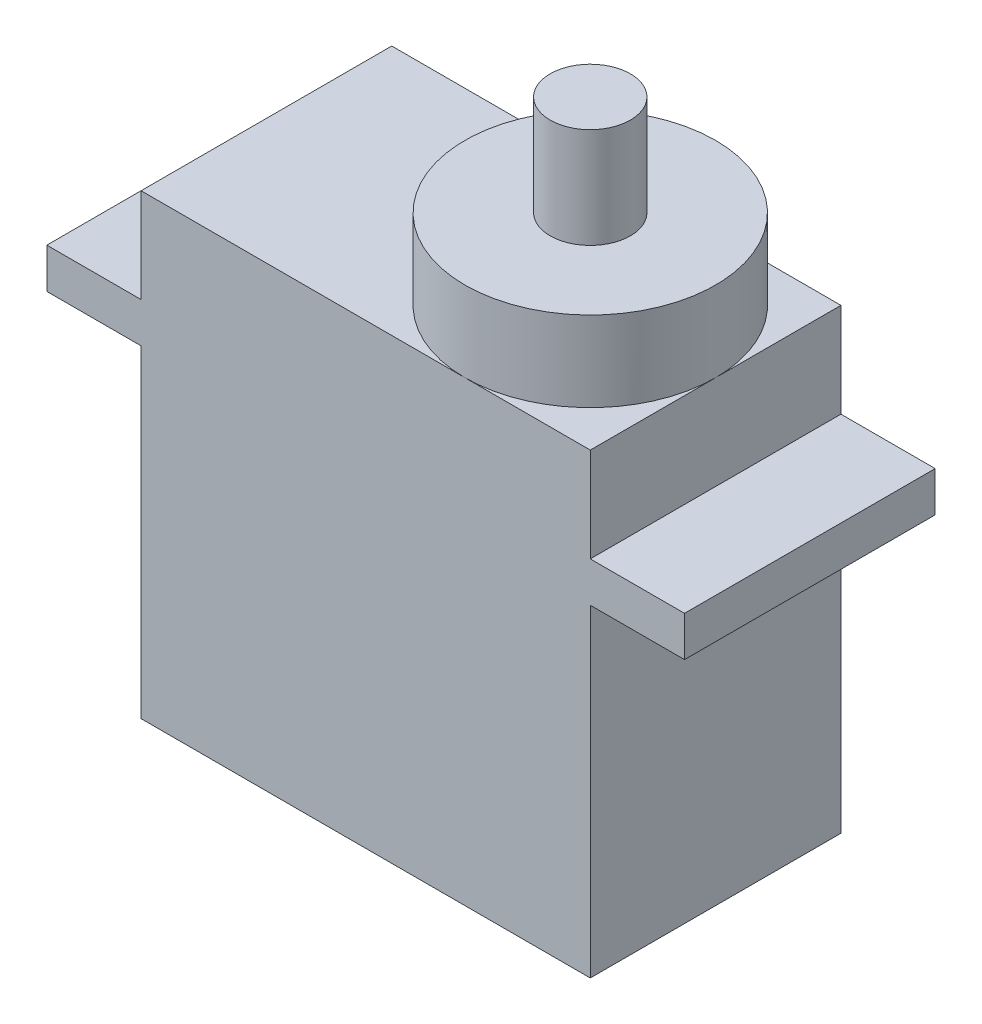
SolidWorks part; units mm, degrees
ref_plane "前视基准面" through (0, 0, 0) normal (0, 0, 1) x (1, 0, 0)
ref_plane "上视基准面" through (0, 0, 0) normal (0, 1, 0) x (1, 0, 0)
ref_plane "右视基准面" through (0, 0, 0) normal (1, 0, 0) x (0, 0, -1)
sketch "草图1" plane through (0, 0, 0) normal (0, 0, 1) x (1, 0, 0)
  line L1 (11.2, -11.4) -> (-11.2, -11.4)
  line L2 (11.2, -11.4) -> (11.2, 11.4)
  line L3 (11.2, 11.4) -> (-11.2, 11.4)
  line L4 (-11.2, -11.4) -> (-11.2, 11.4)
  line L5 (0, 11.4) -> (0, -11.4) construction
  line L6 (11.2, 0) -> (-11.2, 0) construction
  point P0 (0, 0)
  dimension "D1" = 22.8
  dimension "D2" = 22.4
extrude "凸台-拉伸1" add sketch "草图1" along normal mid plane 12.5
sketch "草图4" plane through (0, 0, 6.25) normal (0, 0, 1) x (1, 0, 0)
  line L0 (-11.2, 11.4) -> (-11.2, -11.4) construction
  line L1 (-11.2, 4.7) -> (-15.9, 4.7)
  line L2 (-15.9, 4.7) -> (-15.9, 6.7)
  line L3 (-15.9, 6.7) -> (-11.2, 6.7)
  line L4 (-11.2, 6.7) -> (-11.2, 4.7)
  line L5 (0, 5.6468) -> (0, 0) construction
  line L6 (11.2, 6.7) -> (11.2, 4.7)
  line L7 (15.9, 6.7) -> (11.2, 6.7)
  line L8 (15.9, 4.7) -> (15.9, 6.7)
  line L9 (11.2, 4.7) -> (15.9, 4.7)
  line L10 (-11.2, -11.4) -> (11.2, -11.4) construction
  dimension "D1" = 31.8
  dimension "D2" = 2
  dimension "D3" = 16.1
extrude "凸台-拉伸2" add sketch "草图4" against normal blind 12.5
sketch "草图5" plane through (0, 11.4, 0) normal (0, 1, 0) x (1, 0, 0)
  line L0 (11.2, 6.25) -> (11.2, -6.25) construction
  line L1 (11.2, 6.25) -> (-11.2, 6.25) construction
  line L2 (11.2, -6.25) -> (-11.2, -6.25) construction
  circle A0 centre (4.95, 0) radius 6.25
extrude "凸台-拉伸3" add sketch "草图5" along normal blind 4
sketch "草图6" plane through (0, 15.4, 0) normal (0, 1, 0) x (1, 0, 0)
  circle A0 centre (4.95, 0) radius 2
  circle A1 centre (4.95, 0) radius 6.25 construction
  dimension "D1" = 4
extrude "凸台-拉伸4" add sketch "草图6" along normal blind 5
